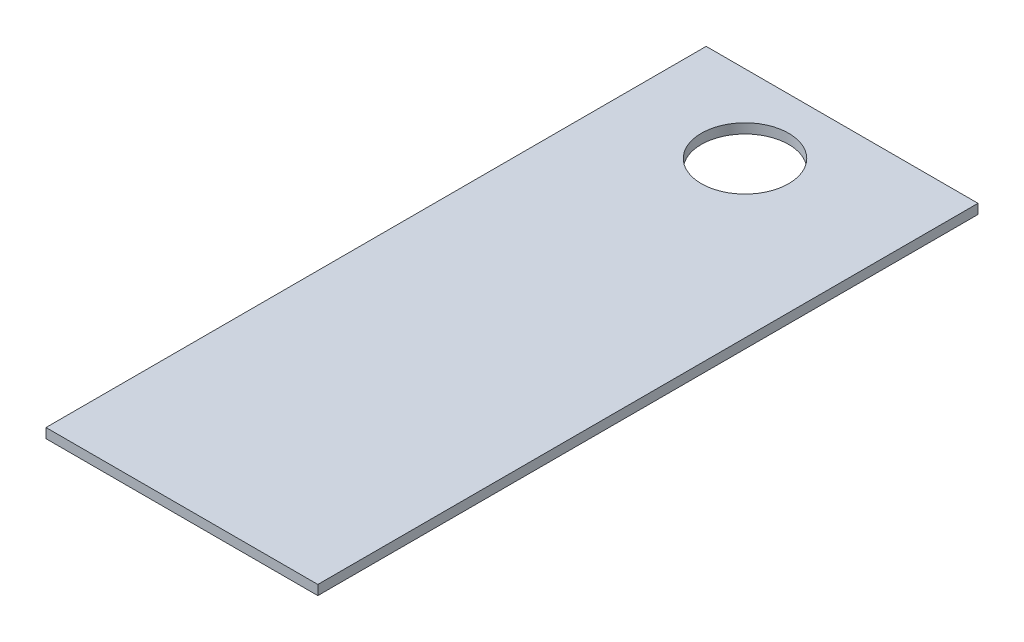
SolidWorks part; units mm, degrees
ref_plane "Front Plane" through (0, 0, 0) normal (0, 0, 1) x (1, 0, 0)
ref_plane "Top Plane" through (0, 0, 0) normal (0, 1, 0) x (1, 0, 0)
ref_plane "Right Plane" through (0, 0, 0) normal (1, 0, 0) x (0, 0, -1)
sketch "Sketch1" plane through (0, 0, 0) normal (0, 1, 0) x (1, 0, 0)
  line L0 (-6.35, 82.55) -> (44.45, 82.55) construction
  line L1 (-44.45, -107.95) -> (44.45, -107.95)
  line L2 (-44.45, -107.95) -> (-44.45, 107.95)
  line L3 (-44.45, 107.95) -> (44.45, 107.95)
  line L4 (44.45, -107.95) -> (44.45, 107.95)
  line L5 (-44.45, -107.95) -> (44.45, 107.95) construction
  line L6 (-44.45, 107.95) -> (44.45, -107.95) construction
  line L7 (-6.35, 107.95) -> (-6.35, 82.55) construction
  circle A0 centre (-6.35, 82.55) radius 14.2875
  point P0 (0, 0)
  dimension "D3" = 28.575
  dimension "D1" = 215.9
  dimension "D2" = 88.9
  dimension "D4" = 38.1
  dimension "D5" = 190.5
extrude "Boss-Extrude1" add sketch "Sketch1" along normal blind 3.175
